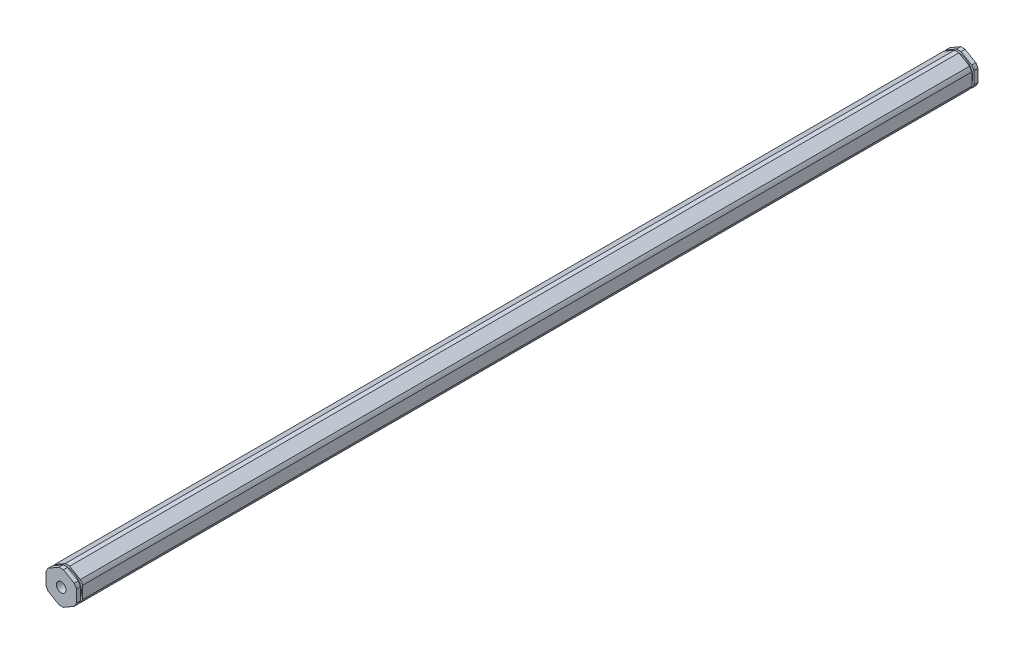
SolidWorks part; units mm, degrees
ref_plane "Front Plane" through (0, 0, 0) normal (0, 0, 1) x (1, 0, 0)
ref_plane "Top Plane" through (0, 0, 0) normal (0, 1, 0) x (1, 0, 0)
ref_plane "Right Plane" through (0, 0, 0) normal (1, 0, 0) x (0, 0, -1)
sketch "Sketch1" plane through (0, 0, 0) normal (0, 0, 1) x (1, 0, 0)
  line L1 (0, 7.3323) -> (-6.35, 3.6662)
  line L2 (-6.35, 3.6662) -> (-6.35, -3.6662)
  line L3 (-6.35, -3.6662) -> (0, -7.3323)
  line L4 (0, -7.3323) -> (6.35, -3.6662)
  line L5 (6.35, -3.6662) -> (6.35, 3.6662)
  line L6 (6.35, 3.6662) -> (0, 7.3323)
  circle A0 centre (0, 0) radius 6.35 construction
  circle A1 centre (0, 0) radius 6.858
  dimension "D1" = 12.7
  dimension "D2" = 13.716
extrude "Boss-Extrude1" add sketch "Sketch1" along normal mid plane 376.809 contours L5 A1 L6 L1 L2 L3 L4
hole_wizard "#10-32 Tapped Hole1" positions "3DSketch1" profile "Sketch2" tap size "#10-32" standard "ANSI Inch"
sketch3d "3DSketch1"
  line L0 (0, 0, 188.4045) -> (0, 0, -188.4045) construction
  line L1 (0, 0, 188.4045) -> (0, 0, -188.4045) construction
  point P0 (0, 0, 188.4045)
  point P4 (0, 0, -188.4045)
sketch "Sketch2" plane through (0, 0, 188.4045) normal (1, 0, 0) x (0, -1, 0)
  line L0 (0, 0) -> (0, 17.5608)
  line L1 (0, 17.5608) -> (2.0193, 16.3474)
  line L2 (2.0193, 16.3474) -> (2.0193, 0)
  line L5 (2.0193, 0) -> (0, 0)
  line L10 (0, 17.5608) -> (-2.0193, 16.3474) construction
  line L11 (0, -6.35) -> (0, 107.95) construction
  dimension "Tap Drill Dia." = 4.0386
  dimension "Tap Drill Depth" = 16.3474
  dimension "Drill Angle" = 118
cosmetic thread "Hole Thread1" parameters "D1"=13.97, "D2"=4.826
cosmetic thread "Hole Thread2" parameters "D1"=13.97, "D2"=4.826
sketch "Sketch3" plane through (0, 0, 0) normal (1, 0, 0) x (0, 0, -1)
  line L0 (-175.1574, 0) -> (-171.1173, 0) construction
  line L1 (188.4045, 6.858) -> (-188.4045, 6.858) construction
  line L2 (-186.69, 6.858) -> (-185.801, 6.858)
  line L3 (-186.69, 6.858) -> (-186.69, 5.8547)
  line L4 (-186.69, 5.8547) -> (-185.801, 5.8547)
  line L5 (-185.801, 6.858) -> (-185.801, 5.8547)
  dimension "D1" = 0.889
  dimension "D2" = 5.8547
  dimension "D3" = 1.7145
revolve "Cut-Revolve1" cut sketch "Sketch3" angle 360 about L0
mirror "Mirror1" about plane through (0, 0, 0) normal (0, 0, 1) of "Cut-Revolve1"
